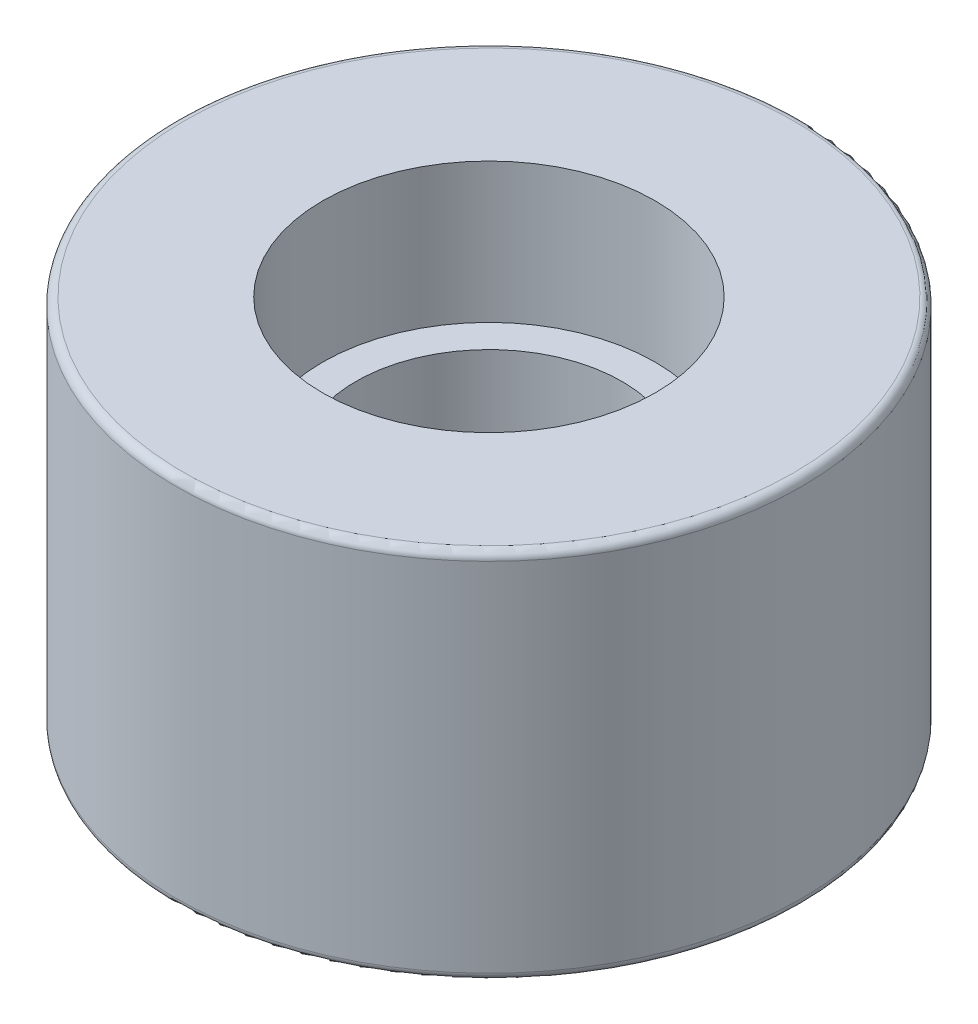
SolidWorks part; units mm, degrees
ref_plane "Płaszczyzna przednia" through (0, 0, 0) normal (0, 0, 1) x (1, 0, 0)
ref_plane "Płaszczyzna górna" through (0, 0, 0) normal (0, 1, 0) x (1, 0, 0)
ref_plane "Płaszczyzna prawa" through (0, 0, 0) normal (1, 0, 0) x (0, 0, -1)
sketch "Szkic1" plane through (0, 0, 0) normal (0, 0, 1) x (1, 0, 0)
  line L0 (0, 0) -> (0, 28) construction
  line L1 (-12.5, 28) -> (-22.9, 28)
  line L2 (-23.5, 27.4) -> (-23.5, 0.6)
  line L3 (-22.9, 0) -> (-13.5, 0)
  line L4 (-13.5, 0) -> (-13.5, 10.5)
  line L5 (-12.5, 17.5) -> (-10, 17.5)
  line L6 (-10, 17.5) -> (-10, 10.5)
  line L7 (-10, 10.5) -> (-13.5, 10.5)
  line L8 (-12.5, 28) -> (-12.5, 17.5)
  arc A0 (-22.9, 28) -> (-23.5, 27.4) centre (-22.9, 27.4) ccw
  arc A1 (-23.5, 0.6) -> (-22.9, 0) centre (-22.9, 0.6) ccw
  point P13 (-23.5, 28)
  point P16 (-23.5, 0)
  dimension "D6" = 0.6
  dimension "D1" = 12.5
  dimension "D2" = 23.5
  dimension "D3" = 28
  dimension "D4" = 7
  dimension "D5" = 13.5
  dimension "D7" = 10
revolve "Obrót1" add sketch "Szkic1" angle 360 about L0
